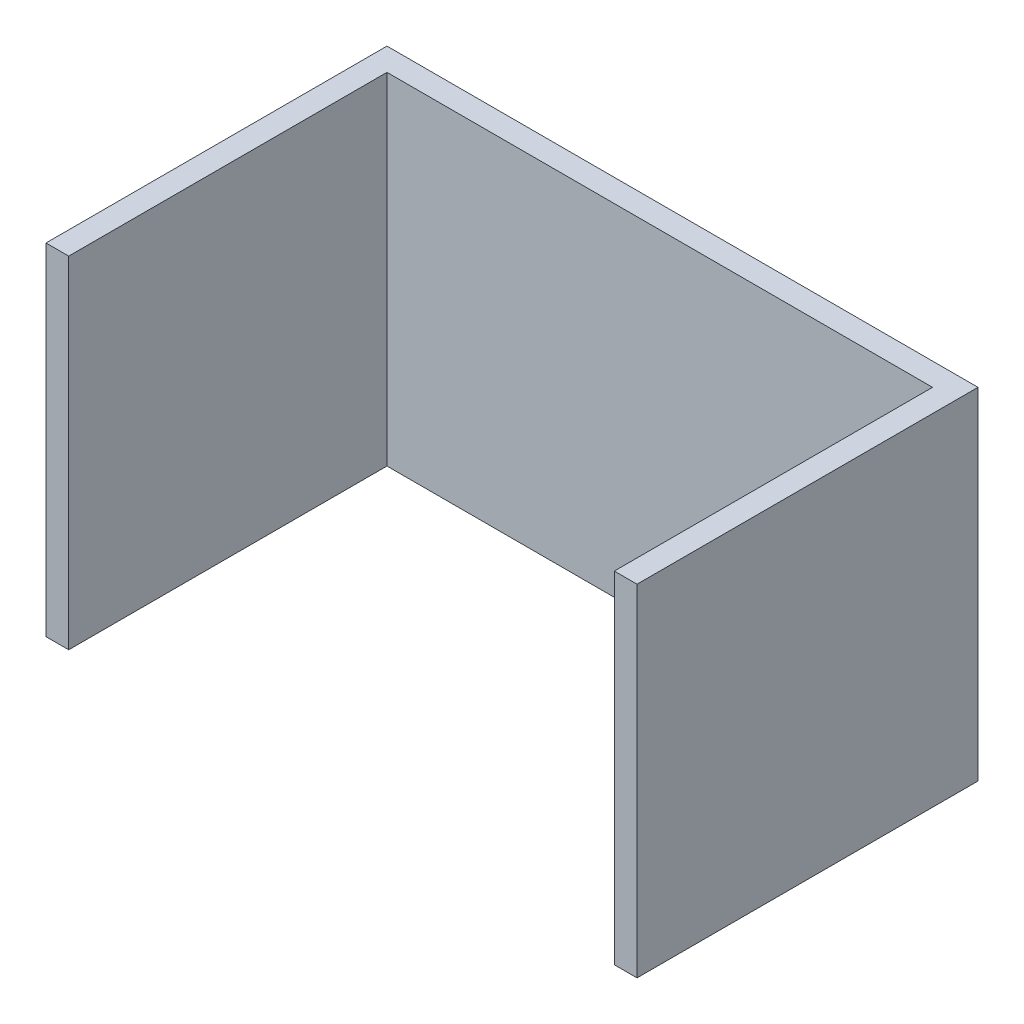
SolidWorks part; units mm, degrees
material "Plastique personnalisé"
ref_plane "Plan de face" through (0, 0, 0) normal (0, 0, 1) x (1, 0, 0)
ref_plane "Plan de dessus" through (0, 0, 0) normal (0, 1, 0) x (1, 0, 0)
ref_plane "Plan de droite" through (0, 0, 0) normal (1, 0, 0) x (0, 0, -1)
sketch "Esquisse1" plane through (0, 0, 0) normal (0, 1, 0) x (1, 0, 0)
  line L1 (-11.5779, -1.404) -> (40.4221, -1.404)
  line L2 (-11.5779, -1.404) -> (-11.5779, 28.596)
  line L3 (-11.5779, 28.596) -> (40.4221, 28.596)
  line L4 (40.4221, -1.404) -> (40.4221, 28.596)
  dimension "D1" = 52
  dimension "D2" = 30
extrude "Boss.-Extru.1" add sketch "Esquisse1" along normal blind 30
sketch "Esquisse2" plane through (0, 30, 0) normal (0, 1, 0) x (1, 0, 0)
  line L0 (-11.5779, 28.596) -> (-11.5779, -1.404) construction
  line L1 (-9.5779, 26.596) -> (38.4221, 26.596)
  line L2 (-9.5779, 26.596) -> (-9.5779, -6.7221)
  line L3 (-9.5779, -6.7221) -> (38.4221, -6.7221)
  line L4 (38.4221, 26.596) -> (38.4221, -6.7221)
  line L5 (40.4221, -1.404) -> (40.4221, 28.596) construction
  line L6 (40.4221, 28.596) -> (-11.5779, 28.596) construction
  dimension "D1" = 2
  dimension "D2" = 2
  dimension "D3" = 2
extrude "Enlèv. mat.-Extru.1" cut sketch "Esquisse2" against normal blind 47
